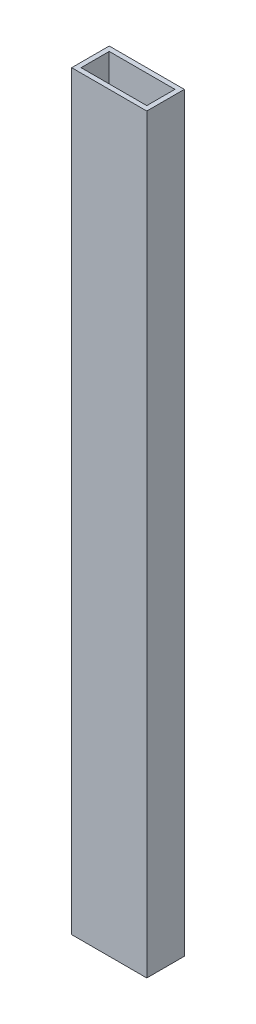
SolidWorks part; units mm, degrees
ref_plane "Front Plane" through (0, 0, 0) normal (0, 0, 1) x (1, 0, 0)
ref_plane "Top Plane" through (0, 0, 0) normal (0, 1, 0) x (1, 0, 0)
ref_plane "Right Plane" through (0, 0, 0) normal (1, 0, 0) x (0, 0, -1)
sketch "Sketch1" plane through (0, 0, 0) normal (0, 1, 0) x (1, 0, 0)
  line L0 (22.225, 9.525) -> (-22.225, 9.525)
  line L1 (25.4, -12.7) -> (-25.4, -12.7)
  line L2 (25.4, -12.7) -> (25.4, 12.7)
  line L3 (25.4, 12.7) -> (-25.4, 12.7)
  line L4 (-25.4, -12.7) -> (-25.4, 12.7)
  line L5 (25.4, -12.7) -> (-25.4, 12.7) construction
  line L6 (25.4, 12.7) -> (-25.4, -12.7) construction
  line L7 (-22.225, -9.525) -> (-22.225, 9.525)
  line L8 (22.225, -9.525) -> (-22.225, -9.525)
  line L9 (22.225, -9.525) -> (22.225, 9.525)
  point P0 (0, 0)
  dimension "D1" = 50.8
  dimension "D2" = 25.4
  dimension "D3" = 3.175
extrude "Boss-Extrude1" add sketch "Sketch1" along normal mid plane 508
